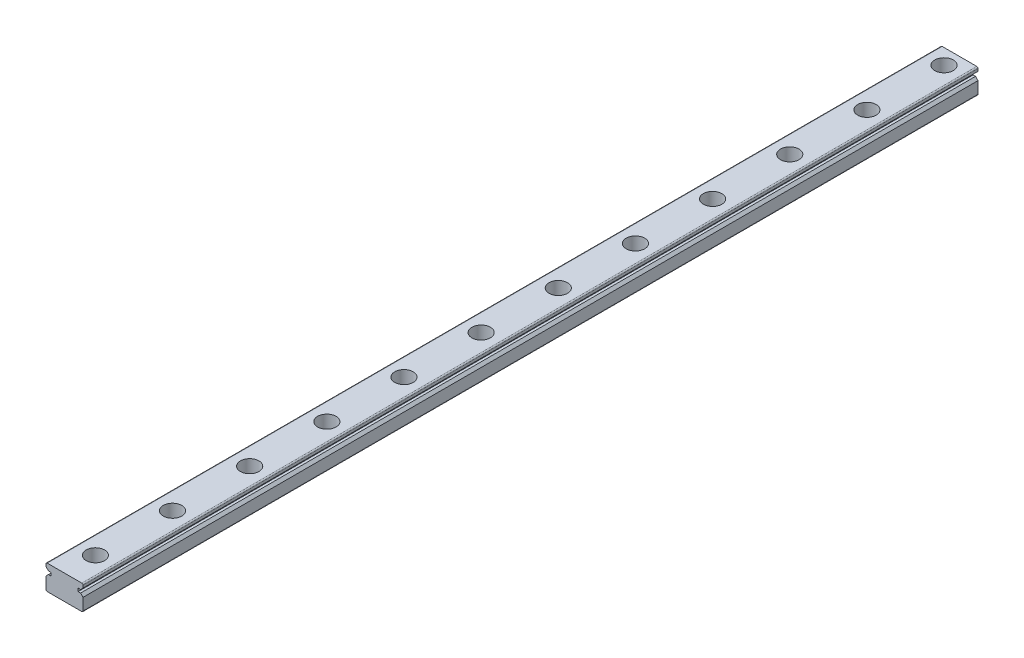
SolidWorks part; units mm, degrees
ref_plane "Front Plane" through (0, 0, 0) normal (0, 0, 1) x (1, 0, 0)
ref_plane "Top Plane" through (0, 0, 0) normal (0, 1, 0) x (1, 0, 0)
ref_plane "Right Plane" through (0, 0, 0) normal (1, 0, 0) x (0, 0, -1)
sketch "Sketch1" plane through (0, 0, 0) normal (0, 0, 1) x (1, 0, 0)
  line L0 (0, -1000) -> (0, 1.5) construction
  line L1 (-5.6, 4) -> (5.6, 4)
  line L2 (-6, 3.6) -> (-6, 2.8)
  line L3 (-5.6, -4) -> (5.6, -4)
  line L4 (6, 3.6) -> (6, 2.8)
  line L5 (-6, 4) -> (6, -4) construction
  line L6 (-6, -4) -> (6, 4) construction
  line L7 (6, 0.2) -> (6, -3.6)
  line L8 (-5.2, 2) -> (-4.4, 2)
  line L9 (-4.4, 2) -> (-4.4, 1)
  line L10 (-5.2, 1) -> (-4.4, 1)
  line L11 (4.4, 2) -> (4.4, 1)
  line L14 (-6, 0.2) -> (-6, -3.6)
  line L15 (4.4, 2) -> (5.2, 2)
  line L16 (4.4, 1) -> (5.2, 1)
  line L17 (0, 1.5) -> (0, 1001.8645) construction
  line L18 (-6, 2.8) -> (-5.2, 2)
  line L19 (-6, 0.2) -> (-5.2, 1)
  line L20 (5.2, 2) -> (6, 2.8)
  line L21 (5.2, 1) -> (6, 0.2)
  arc A0 (-6, -3.6) -> (-5.6, -4) centre (-5.6, -3.6) ccw
  arc A1 (5.6, -4) -> (6, -3.6) centre (5.6, -3.6) ccw
  arc A2 (5.6, 4) -> (6, 3.6) centre (5.6, 3.6) cw
  arc A3 (-5.6, 4) -> (-6, 3.6) centre (-5.6, 3.6) ccw
  point P0 (0, 0)
  point P13 (-6, 2)
  point P14 (6, 2)
  point P15 (6, 1)
  point P16 (-6, 1)
  dimension "D5" = 0.4
  dimension "D1" = 12
  dimension "D2" = 8
  dimension "D3" = 8.8
  dimension "D4" = 5
  dimension "D6" = 2
  dimension "D7" = 5
  dimension "D8" = 4.4
extrude "Boss-Extrude1" add sketch "Sketch1" along normal blind 290
sketch "Sketch2" plane through (0, 4, 0) normal (0, 1, 0) x (1, 0, 0)
  line L0 (5.6, -290) -> (-5.6, -290) construction
  circle A0 centre (0, -280) radius 3
  circle A1 centre (0, -255) radius 3
  circle A2 centre (0, -230) radius 3
  circle A3 centre (0, -205) radius 3
  circle A4 centre (0, -180) radius 3
  circle A5 centre (0, -155) radius 3
  circle A6 centre (0, -130) radius 3
  circle A7 centre (0, -105) radius 3
  circle A8 centre (0, -80) radius 3
  circle A9 centre (0, -55) radius 3
  circle A10 centre (0, -30) radius 3
  circle A11 centre (0, -5) radius 3
  circle A12 centre (0, 20) radius 3
  circle A13 centre (0, 45) radius 3
  circle A14 centre (0, 70) radius 3
  circle A15 centre (0, 95) radius 3
  circle A16 centre (0, 120) radius 3
  circle A17 centre (0, 145) radius 3
  point P39 (0, -290)
  dimension "D1" = 10
  dimension "D2" = 6
  dimension "D3" = 18
extrude "Cut-Extrude1" cut sketch "Sketch2" against normal blind 4.5
sketch "Sketch3" plane through (0, 4, 0) normal (0, 1, 0) x (1, 0, 0)
  line L0 (5.6, -290) -> (-5.6, -290) construction
  circle A2 centre (0, -280.0015) radius 1.75
  circle A3 centre (0, -255.0015) radius 1.75
  circle A4 centre (0, -230.0015) radius 1.75
  circle A5 centre (0, -205.0015) radius 1.75
  circle A6 centre (0, -180.0015) radius 1.75
  circle A7 centre (0, -155.0015) radius 1.75
  circle A8 centre (0, -130.0015) radius 1.75
  circle A9 centre (0, -105.0015) radius 1.75
  circle A10 centre (0, -80.0015) radius 1.75
  circle A11 centre (0, -55.0015) radius 1.75
  circle A12 centre (0, -30.0015) radius 1.75
  circle A13 centre (0, -5.0015) radius 1.75
  circle A14 centre (0, 19.9985) radius 1.75
  circle A15 centre (0, 44.9985) radius 1.75
  circle A16 centre (0, 69.9985) radius 1.75
  point P6 (0, -290)
  dimension "D1" = 3.5
  dimension "D2" = 9.9985
  dimension "D3" = 15
extrude "Cut-Extrude2" cut sketch "Sketch3" against normal through all
